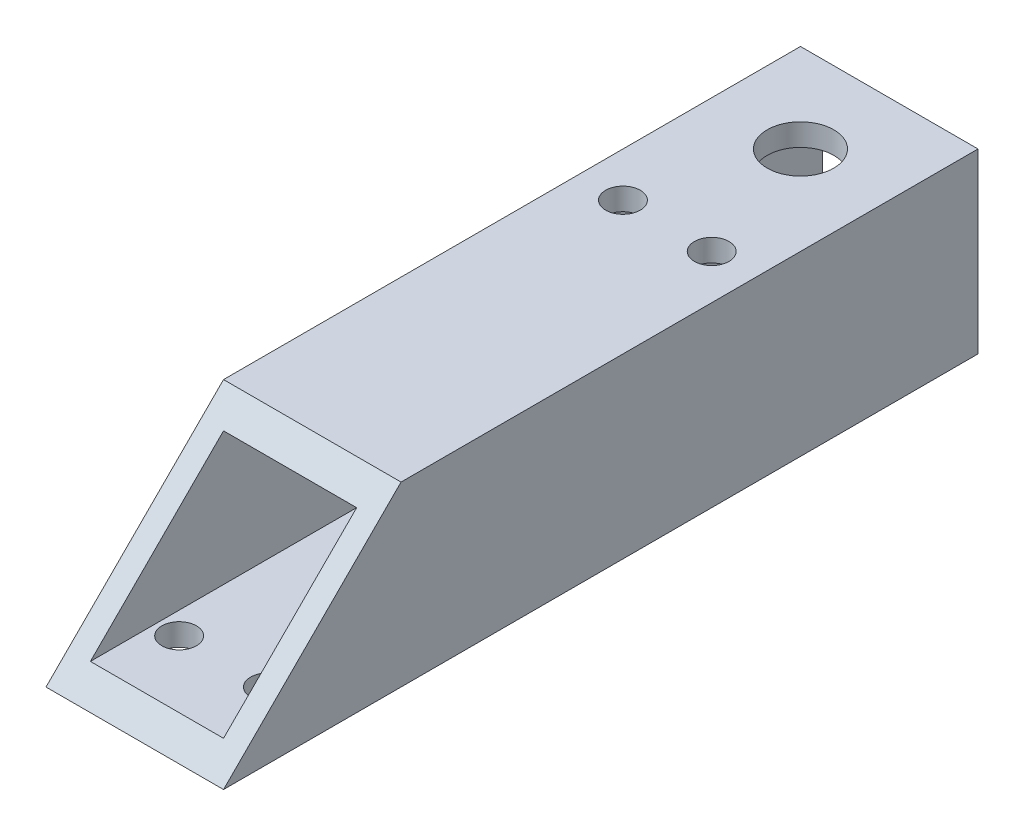
SolidWorks part; units mm, degrees
material "1060 Alloy"
ref_plane "Front Plane" through (0, 0, 0) normal (0, 0, 1) x (1, 0, 0)
ref_plane "Top Plane" through (0, 0, 0) normal (0, 1, 0) x (1, 0, 0)
ref_plane "Right Plane" through (0, 0, 0) normal (1, 0, 0) x (0, 0, -1)
sketch "Sketch1" plane through (0, 0, 0) normal (0, 0, 1) x (1, 0, 0)
  line L1 (-12.7, -12.7) -> (12.7, -12.7)
  line L2 (-12.7, -12.7) -> (-12.7, 12.7)
  line L3 (-12.7, 12.7) -> (12.7, 12.7)
  line L4 (12.7, -12.7) -> (12.7, 12.7)
  line L5 (-12.7, -12.7) -> (12.7, 12.7) construction
  line L6 (-12.7, 12.7) -> (12.7, -12.7) construction
  point P0 (0, 0)
  dimension "D1" = 25.4
  dimension "D2" = 25.4
extrude "Boss-Extrude1" add sketch "Sketch1" along normal blind 107.95 contours L2 L1 L4 L3
sketch "Sketch2" plane through (0, 0, 107.95) normal (0, 0, 1) x (1, 0, 0)
  line L1 (-9.525, -9.525) -> (9.525, -9.525)
  line L2 (-9.525, -9.525) -> (-9.525, 9.525)
  line L3 (-9.525, 9.525) -> (9.525, 9.525)
  line L4 (9.525, -9.525) -> (9.525, 9.525)
  line L5 (-9.525, -9.525) -> (9.525, 9.525) construction
  line L6 (-9.525, 9.525) -> (9.525, -9.525) construction
  point P0 (0, 0)
  dimension "D1" = 19.05
  dimension "D2" = 19.05
extrude "Cut-Extrude1" cut sketch "Sketch2" against normal through all
sketch "Sketch4" plane through (12.7, 0, 0) normal (1, 0, 0) x (0, 0, -1)
  line L0 (-107.95, 12.7) -> (-82.55, 12.7)
  line L1 (-107.95, 12.7) -> (0, 12.7) construction
  line L2 (-82.55, 12.7) -> (-107.95, -12.7)
  line L3 (-107.95, -12.7) -> (-107.95, 12.7)
  dimension "D1" = 25.4
extrude "Cut-Extrude2" cut sketch "Sketch4" against normal through all
sketch "Sketch5" plane through (0, -12.7, 0) normal (0, -1, 0) x (1, 0, 0)
  line L0 (-12.7, 107.95) -> (12.7, 107.95) construction
  line L1 (-12.7, 107.95) -> (-12.7, 0) construction
  line L3 (0, 107.95) -> (0, 73.3565) construction
  circle A0 centre (-6.35, 95.25) radius 2.4765
  circle A1 centre (6.35, 95.25) radius 2.4765
  dimension "D1" = 4.953
  dimension "D2" = 12.7
  dimension "D3" = 6.35
extrude "Cut-Extrude3" cut sketch "Sketch5" against normal through all
sketch "Sketch7" plane through (0, 12.7, 0) normal (0, 1, 0) x (1, 0, 0)
  line L0 (-12.7, 0) -> (12.7, 0) construction
  line L1 (-12.7, -82.55) -> (-12.7, 0) construction
  circle A0 centre (0, -12.7) radius 4.7625
  dimension "D1" = 9.525
  dimension "D2" = 12.7
  dimension "D3" = 12.7
extrude "Cut-Extrude5" cut sketch "Sketch7" against normal through all
sketch "Sketch8" plane through (0, -12.7, 0) normal (0, -1, 0) x (1, 0, 0)
  line L0 (-12.7, 0) -> (12.7, 0) construction
  line L1 (12.7, 107.95) -> (12.7, 0) construction
  circle A2 centre (6.35, 31.75) radius 2.4765
  circle A3 centre (-6.35, 31.75) radius 2.4765
  dimension "D4" = 4.953
  dimension "D1" = 31.75
  dimension "D2" = 6.35
  dimension "D3" = 12.7
extrude "Cut-Extrude6" cut sketch "Sketch8" against normal through all
